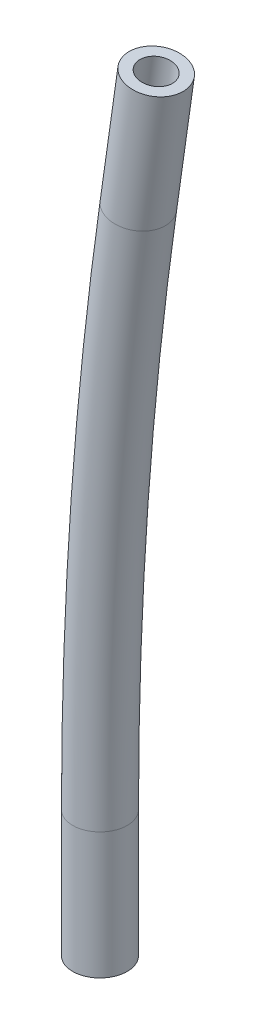
SolidWorks part; units mm, degrees
material "Nylon 6/10"
ref_plane "Front Plane" through (0, 0, 0) normal (0, 0, 1) x (1, 0, 0)
ref_plane "Top Plane" through (0, 0, 0) normal (0, 1, 0) x (1, 0, 0)
ref_plane "Right Plane" through (0, 0, 0) normal (1, 0, 0) x (0, 0, -1)
sketch "Sketch1" plane through (0, 0, 0) normal (0, 0, 1) x (1, 0, 0)
  line L0 (0, 0) -> (0, 14.732)
  line L1 (4.4721, 77.8935) -> (6.5478, 92.4785)
  arc A0 (0, 14.732) -> (4.4721, 77.8935) centre (448.2676, 14.732) cw
  dimension "D1" = 8.1
  dimension "D2" = 14.732
  dimension "D3" = 92.71
sketch "Sketch2" plane through (0, 0, 0) normal (0, 1, 0) x (1, 0, 0)
  circle A0 centre (0, 0) radius 3.175
  circle A1 centre (0, 0) radius 1.905
  dimension "D1" = 6.35
  dimension "D2" = 3.81
sweep "Sweep1" add profiles "Sketch2" path "Sketch1"
